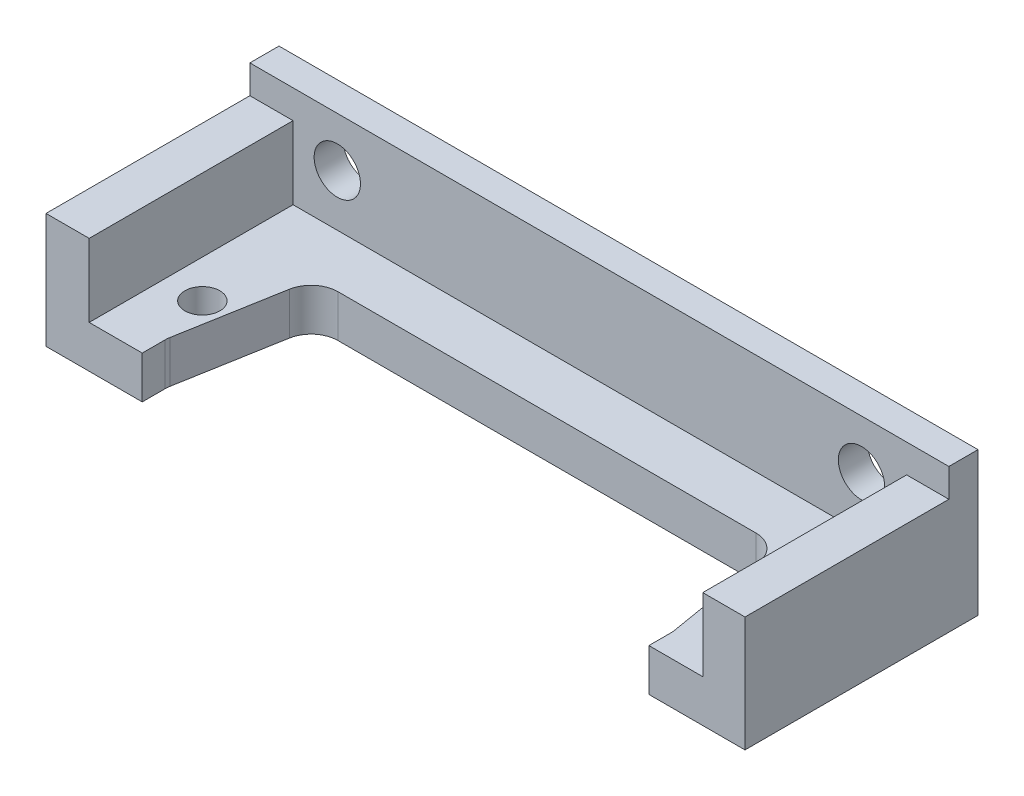
SolidWorks part; units mm, degrees
ref_plane "Front Plane" through (0, 0, 0) normal (0, 0, 1) x (1, 0, 0)
ref_plane "Top Plane" through (0, 0, 0) normal (0, 1, 0) x (1, 0, 0)
ref_plane "Right Plane" through (0, 0, 0) normal (1, 0, 0) x (0, 0, -1)
sketch "Sketch1" plane through (0, 0, 0) normal (0, 0, 1) x (1, 0, 0)
  line L0 (-101.6488, 206.2152) -> (-45.7688, 206.2152)
  line L1 (-45.7688, 206.2152) -> (-45.7688, 216.197)
  line L2 (-45.7688, 216.197) -> (-101.6488, 216.197)
  line L3 (-101.6488, 216.197) -> (-101.6488, 206.2152)
  circle A1 centre (-96.5654, 211.879) radius 2.0193
  circle A2 centre (-50.8488, 211.879) radius 2.0193
  dimension "D5" = 4.0386
  dimension "D6" = 4.0386
  dimension "D7" = 5.08
  dimension "D8" = 4.318
  dimension "D9" = 4.318
  dimension "D10" = 5.0834
  dimension "D1" = 55.88
  dimension "D2" = 9.9818
extrude "Boss-Extrude1" add sketch "Sketch1" along normal blind 2.54
sketch "Sketch2" plane through (0, 0, 2.54) normal (0, 0, 1) x (1, 0, 0)
  line L0 (-101.6488, 206.2152) -> (-101.6488, 207.3674)
  line L1 (-101.6488, 207.3674) -> (-45.7688, 207.3674)
  line L2 (-45.7688, 207.3674) -> (-45.7688, 206.2152)
  line L4 (-101.6488, 216.197) -> (-101.6488, 206.2152)
  line L5 (-101.6488, 206.2152) -> (-45.7688, 206.2152)
  line L6 (-45.7688, 206.2152) -> (-45.7688, 216.197)
  line L7 (-45.7688, 216.197) -> (-101.6488, 216.197)
  line L8 (-101.6488, 216.197) -> (-101.6488, 206.2152)
  line L9 (-101.6488, 206.2152) -> (-45.7688, 206.2152)
  line L10 (-45.7688, 206.2152) -> (-45.7688, 216.197)
  line L11 (-45.7688, 216.197) -> (-101.6488, 216.197)
  line M7 (-101.6488, 216.197) -> (-101.6488, 206.2152)
  line M8 (-101.6488, 206.2152) -> (-45.7688, 206.2152)
  line M9 (-45.7688, 206.2152) -> (-45.7688, 216.197)
  dimension "D2" = 8.8296
  dimension "D1" = 0
extrude "Boss-Extrude2" add sketch "Sketch2" along normal blind 17.78 contours L1 M7 M8 M9
sketch "Sketch3" plane through (0, 207.3674, 0) normal (0, 1, 0) x (1, 0, 0)
  line L0 (-101.6488, -20.32) -> (-100.4223, -20.32)
  line L1 (-100.4223, -20.32) -> (-100.4223, -2.54)
  line L2 (-100.4223, -2.54) -> (-101.6488, -2.54)
  line L3 (-45.7688, -20.32) -> (-46.9126, -20.32)
  line L4 (-45.7688, -2.54) -> (-101.6488, -2.54)
  line L5 (-101.6488, -2.54) -> (-101.6488, -20.32)
  line L6 (-101.6488, -20.32) -> (-45.7688, -20.32)
  line L7 (-45.7688, -20.32) -> (-45.7688, -2.54)
  line L8 (-45.7688, -2.54) -> (-101.6488, -2.54)
  line L9 (-101.6488, -2.54) -> (-101.6488, -20.32)
  line L10 (-101.6488, -20.32) -> (-45.7688, -20.32)
  line L11 (-45.7688, -20.32) -> (-45.7688, -2.54)
  line L12 (-46.9126, -20.32) -> (-46.9126, -2.54)
  line L13 (-46.9126, -2.54) -> (-45.7688, -2.54)
  line M8 (-45.7688, -2.54) -> (-101.6488, -2.54)
  line M9 (-101.6488, -2.54) -> (-101.6488, -20.32)
  line M10 (-101.6488, -20.32) -> (-45.7688, -20.32)
  line M11 (-45.7688, -20.32) -> (-45.7688, -2.54)
  dimension "D2" = 1.2265
  dimension "D3" = 1.1438
  dimension "D1" = 0
extrude "Boss-Extrude4" add sketch "Sketch3" along normal blind 6.35 contours L1 M10 M8 M9 | L12 M10 M11 M8
sketch "Sketch4" plane through (0, 207.3674, 0) normal (0, 1, 0) x (1, 0, 0)
  line L1 (-100.4223, -20.32) -> (-100.4223, -2.54) construction
  line L2 (-46.9126, -20.32) -> (-46.9126, -2.54) construction
  line L3 (-100.4223, -20.32) -> (-46.9126, -20.32) construction
  circle A0 centre (-97.1203, -13.7541) radius 1.524
  circle A1 centre (-50.2146, -13.7541) radius 1.524
  dimension "D1" = 3.302
  dimension "D3" = 3.048
  dimension "D5" = 6.5659
  dimension "D2" = 3.302
  dimension "D4" = 6.5659
extrude "Cut-Extrude1" cut sketch "Sketch4" against normal through all
sketch "Sketch5" plane through (0, 207.3674, 0) normal (0, 1, 0) x (1, 0, 0)
  line L0 (-97.1203, -13.7541) -> (-50.2146, -13.7541) construction
  line L1 (-93.8605, -7.1501) -> (-53.4745, -7.1501)
  line L2 (-100.4223, -2.54) -> (-46.9126, -2.54) construction
  line L3 (-73.6675, 6.0198) -> (-73.6675, -20.32) construction
  line L4 (-46.9126, -20.32) -> (-46.9126, -2.54)
  line L5 (-46.9126, -2.54) -> (-100.4223, -2.54)
  line L6 (-100.4223, -2.54) -> (-100.4223, -20.32)
  line L7 (-100.4223, -20.32) -> (-46.9126, -20.32)
  line L8 (-46.9126, -20.32) -> (-46.9126, -2.54)
  line L9 (-46.9126, -2.54) -> (-100.4223, -2.54)
  line L10 (-100.4223, -2.54) -> (-100.4223, -20.32)
  line L11 (-100.4223, -20.32) -> (-46.9126, -20.32)
  line L12 (-93.8605, -7.1501) -> (-95.7953, -18.1229)
  line L13 (-53.4745, -7.1501) -> (-51.6116, -18.2375)
  line L14 (-95.7953, -18.1229) -> (-95.7953, -0.3506) construction
  line L15 (-92.9559, -20.32) -> (-62.9219, -20.32)
  line L16 (-51.6116, -18.2375) -> (-51.6116, -0.4651) construction
  line L17 (-95.7953, -18.1229) -> (-95.7953, -20.32)
  line L18 (-95.7953, -20.32) -> (-51.6116, -20.32)
  line L19 (-51.6116, -20.32) -> (-51.6116, -18.2375)
  line L20 (-73.6675, -20.3581) -> (-73.6675, -7.1501) construction
  circle A0 centre (-97.1203, -13.7541) radius 1.524 construction
  circle A1 centre (-50.2146, -13.7541) radius 1.524 construction
  circle A2 centre (-97.1203, -13.7541) radius 1.524
  circle A3 centre (-50.2146, -13.7541) radius 1.524
  point P25 (-73.6675, -7.1501)
  point P26 (-73.6675, -13.7541)
  dimension "D2" = 10
  dimension "D3" = 1.397
  dimension "D4" = 9.537
  dimension "D5" = 40.386
  dimension "D7" = 6.604
  dimension "D1" = 0
extrude "Cut-Extrude3" cut sketch "Sketch5" against normal through all
sketch "Sketch6" plane through (-101.6488, 0, 0) normal (-1, 0, 0) x (0, 0, 1)
  line L0 (0, 216.197) -> (2.54, 216.197)
  line L1 (2.54, 213.7174) -> (20.32, 213.7174)
  line L2 (20.32, 206.2152) -> (0, 206.2152)
  line L6 (0, 216.197) -> (0, 206.2152)
  line L7 (0, 206.2152) -> (20.32, 206.2152)
  line L8 (20.32, 206.2152) -> (20.32, 213.7174)
  line L9 (20.32, 213.7174) -> (2.54, 213.7174)
  line L10 (2.54, 213.7174) -> (2.54, 216.197)
  line L11 (2.54, 216.197) -> (0, 216.197)
  line L12 (0, 216.197) -> (0, 206.2152)
  line L13 (0, 206.2152) -> (20.32, 206.2152)
  line L14 (20.32, 206.2152) -> (20.32, 213.7174)
  line L15 (20.32, 213.7174) -> (2.54, 213.7174)
  line L16 (2.54, 213.7174) -> (2.54, 216.197)
  line L17 (2.54, 216.197) -> (0, 216.197)
  line M7 (0, 216.197) -> (0, 206.2152)
  line M8 (0, 206.2152) -> (20.32, 206.2152)
  line M9 (20.32, 206.2152) -> (20.32, 213.7174)
  line M10 (20.32, 213.7174) -> (2.54, 213.7174)
  line M11 (2.54, 213.7174) -> (2.54, 216.197)
  line M12 (2.54, 216.197) -> (0, 216.197)
  dimension "D1" = 0
extrude "Boss-Extrude5" add sketch "Sketch6" along normal blind 2.54 contours M12 M7 M8 M9 M10 M11
sketch "Sketch7" plane through (-45.7688, 0, 0) normal (1, 0, 0) x (0, 0, -1)
  line L0 (-20.32, 213.7174) -> (-2.54, 213.7174)
  line L1 (-2.54, 216.197) -> (0, 216.197)
  line L2 (0, 206.2152) -> (-20.32, 206.2152)
  line L6 (-2.54, 216.197) -> (-2.54, 213.7174)
  line L7 (-2.54, 213.7174) -> (-20.32, 213.7174)
  line L8 (-20.32, 213.7174) -> (-20.32, 206.2152)
  line L9 (-20.32, 206.2152) -> (0, 206.2152)
  line L10 (0, 206.2152) -> (0, 216.197)
  line L11 (0, 216.197) -> (-2.54, 216.197)
  line L12 (-2.54, 216.197) -> (-2.54, 213.7174)
  line L13 (-2.54, 213.7174) -> (-20.32, 213.7174)
  line L14 (-20.32, 213.7174) -> (-20.32, 206.2152)
  line L15 (-20.32, 206.2152) -> (0, 206.2152)
  line L16 (0, 206.2152) -> (0, 216.197)
  line L17 (0, 216.197) -> (-2.54, 216.197)
  line M7 (-2.54, 216.197) -> (-2.54, 213.7174)
  line M8 (-2.54, 213.7174) -> (-20.32, 213.7174)
  line M9 (-20.32, 213.7174) -> (-20.32, 206.2152)
  line M10 (-20.32, 206.2152) -> (0, 206.2152)
  line M11 (0, 206.2152) -> (0, 216.197)
  line M12 (0, 216.197) -> (-2.54, 216.197)
  dimension "D1" = 0
extrude "Boss-Extrude6" add sketch "Sketch7" along normal blind 2.54 contours M12 M7 M8 M9 M10 M11
fillet "Fillet1" radius 2.3368 1 edges at (-93.8605, 206.7913, 7.1501)
fillet "Fillet2" radius 2.3368 1 edges at (-53.4745, 206.7913, 7.1501)
fillet "Fillet3" radius 2.3368 1 edges at (-95.7953, 206.7913, 18.1229)
fillet "Fillet4" radius 2.3368 1 edges at (-51.6116, 206.7913, 18.2375)
sketch "Sketch8" plane through (0, 206.2152, 0) normal (0, -1, 0) x (1, 0, 0)
  line L10 (-55.4514, 7.1501) -> (-91.8997, 7.1501)
  line L11 (-94.201, 9.0811) -> (-95.7598, 17.9216)
  line L12 (-95.7953, 18.3273) -> (-95.7953, 20.32)
  line L13 (-95.7953, 20.32) -> (-104.1888, 20.32)
  line L14 (-104.1888, 20.32) -> (-104.1888, 0)
  line L15 (-104.1888, 0) -> (-43.2288, 0)
  line L16 (-43.2288, 0) -> (-43.2288, 20.32)
  line L17 (-43.2288, 20.32) -> (-51.6116, 20.32)
  line L18 (-51.6116, 20.32) -> (-51.6116, 18.4324)
  line L19 (-51.6439, 18.0452) -> (-53.1469, 9.0997)
  line L20 (-55.4514, 7.1501) -> (-91.8997, 7.1501)
  line L21 (-94.201, 9.0811) -> (-95.7598, 17.9216)
  line L22 (-95.7953, 18.3273) -> (-95.7953, 20.32)
  line L23 (-95.7953, 20.32) -> (-104.1888, 20.32)
  line L24 (-104.1888, 20.32) -> (-104.1888, 0)
  line L25 (-104.1888, 0) -> (-43.2288, 0)
  line L26 (-43.2288, 0) -> (-43.2288, 20.32)
  line L27 (-43.2288, 20.32) -> (-51.6116, 20.32)
  line L28 (-51.6116, 20.32) -> (-51.6116, 18.4324)
  line L29 (-51.6439, 18.0452) -> (-53.1469, 9.0997)
  circle A0 centre (-50.2146, 13.7541) radius 1.524 construction
  circle A1 centre (-97.1203, 13.7541) radius 1.524 construction
  circle A2 centre (-50.2146, 13.7541) radius 1.524
  circle A3 centre (-97.1203, 13.7541) radius 1.524
  arc A4 (-94.201, 9.0811) -> (-91.8997, 7.1501) centre (-91.8997, 9.4869) ccw
  arc A5 (-95.7953, 18.3273) -> (-95.7598, 17.9216) centre (-93.4585, 18.3273) ccw
  arc A6 (-51.6439, 18.0452) -> (-51.6116, 18.4324) centre (-53.9484, 18.4324) ccw
  arc A7 (-55.4514, 7.1501) -> (-53.1469, 9.0997) centre (-55.4514, 9.4869) ccw
  arc A8 (-94.201, 9.0811) -> (-91.8997, 7.1501) centre (-91.8997, 9.4869) ccw
  arc A9 (-95.7953, 18.3273) -> (-95.7598, 17.9216) centre (-93.4585, 18.3273) ccw
  arc A10 (-51.6439, 18.0452) -> (-51.6116, 18.4324) centre (-53.9484, 18.4324) ccw
  arc A11 (-55.4514, 7.1501) -> (-53.1469, 9.0997) centre (-55.4514, 9.4869) ccw
  dimension "D1" = 0
extrude "Boss-Extrude7" add sketch "Sketch8" along normal blind 2.54
